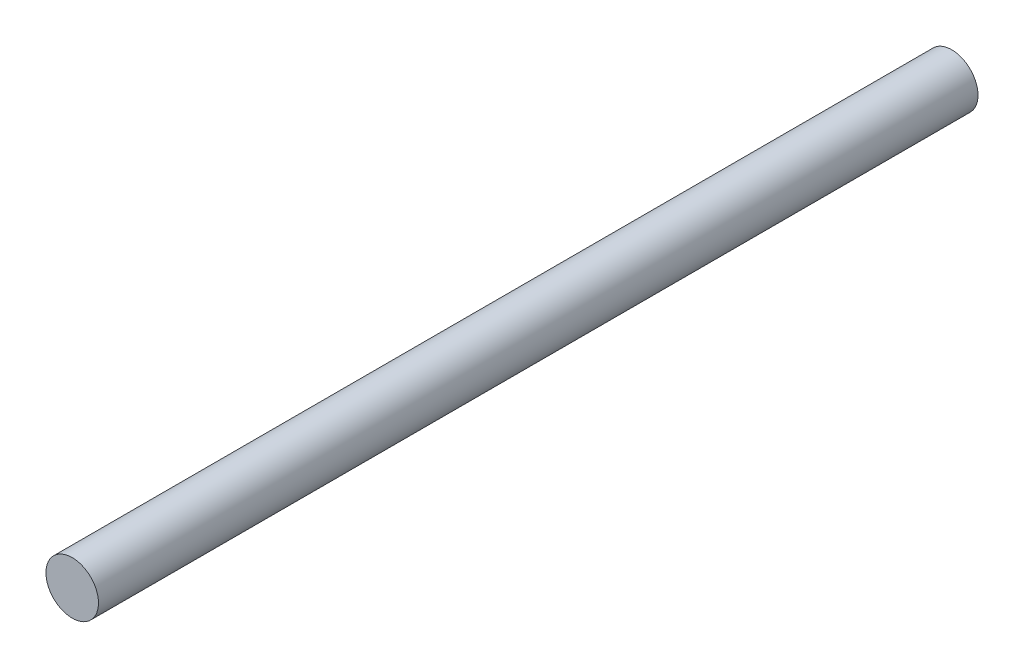
SolidWorks part; units mm, degrees
ref_plane "Front Plane" through (0, 0, 0) normal (0, 0, 1) x (1, 0, 0)
ref_plane "Top Plane" through (0, 0, 0) normal (0, 1, 0) x (1, 0, 0)
ref_plane "Right Plane" through (0, 0, 0) normal (1, 0, 0) x (0, 0, -1)
sketch "Sketch1" plane through (0, 0, 0) normal (0, 0, 1) x (1, 0, 0)
  circle A0 centre (0, 0) radius 4
  dimension "D1" = 8
extrude "Boss-Extrude1" add sketch "Sketch1" along normal blind 134
